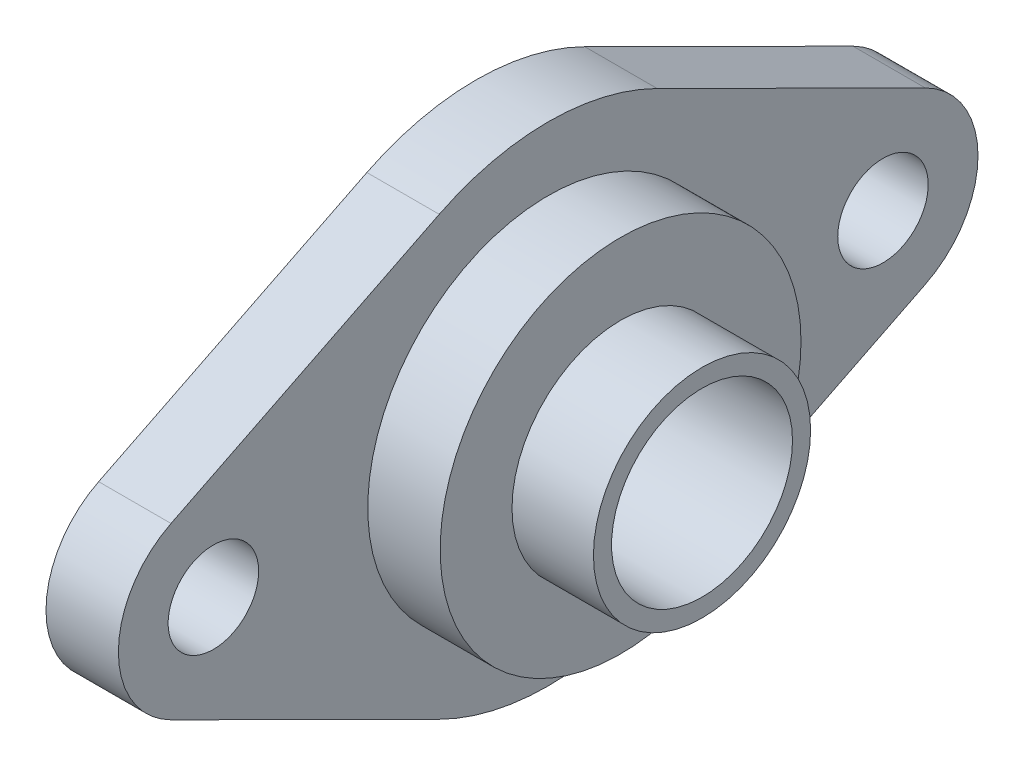
SolidWorks part; units mm, degrees
ref_plane "Front Plane" through (0, 0, 0) normal (0, 0, 1) x (1, 0, 0)
ref_plane "Top Plane" through (0, 0, 0) normal (0, 1, 0) x (1, 0, 0)
ref_plane "Right Plane" through (0, 0, 0) normal (1, 0, 0) x (0, 0, -1)
sketch "Sketch1" plane through (0, 0, 0) normal (1, 0, 0) x (0, 0, -1)
  line L0 (-23.75, 12.2185) -> (-23.75, -16.8311) construction
  line L1 (-20.8412, 4.6991) -> (-6.0203, 12.0833)
  line L2 (-20.8412, -4.6991) -> (-6.0203, -12.0833)
  line L3 (0, 13.5) -> (0, -13.5) construction
  line L4 (23.75, 12.2185) -> (23.75, -16.8311) construction
  line L5 (20.8412, -4.6991) -> (6.0203, -12.0833)
  line L6 (20.8412, 4.6991) -> (6.0203, 12.0833)
  arc A0 (-6.0203, -12.0833) -> (6.0203, -12.0833) centre (0, 0) ccw
  arc A1 (-20.8412, 4.6991) -> (-20.8412, -4.6991) centre (-18.5, 0) ccw
  circle A2 centre (-18.5, 0) radius 2.5
  arc A3 (6.0203, 12.0833) -> (-6.0203, 12.0833) centre (0, 0) ccw
  circle A4 centre (18.5, 0) radius 2.5
  arc A5 (20.8412, 4.6991) -> (20.8412, -4.6991) centre (18.5, 0) cw
  dimension "D2" = 27
  dimension "D3" = 10.5
  dimension "D4" = 5
  dimension "D1" = 23.75
extrude "Boss-Extrude1" add sketch "Sketch1" along normal blind 4
sketch "Sketch2" plane through (4, 0, 0) normal (1, 0, 0) x (0, 0, -1)
  circle A0 centre (0, 0) radius 9.9697
extrude "Boss-Extrude2" add sketch "Sketch2" along normal blind 4
sketch "Sketch3" plane through (8, 0, 0) normal (1, 0, 0) x (0, 0, -1)
  circle A0 centre (0, 0) radius 6
  dimension "D1" = 12
extrude "Boss-Extrude3" add sketch "Sketch3" along normal blind 4.5
sketch "Sketch4" plane through (12.5, 0, 0) normal (1, 0, 0) x (0, 0, -1)
  circle A0 centre (0, 0) radius 5
  dimension "D1" = 10
extrude "Cut-Extrude1" cut sketch "Sketch4" against normal through all
